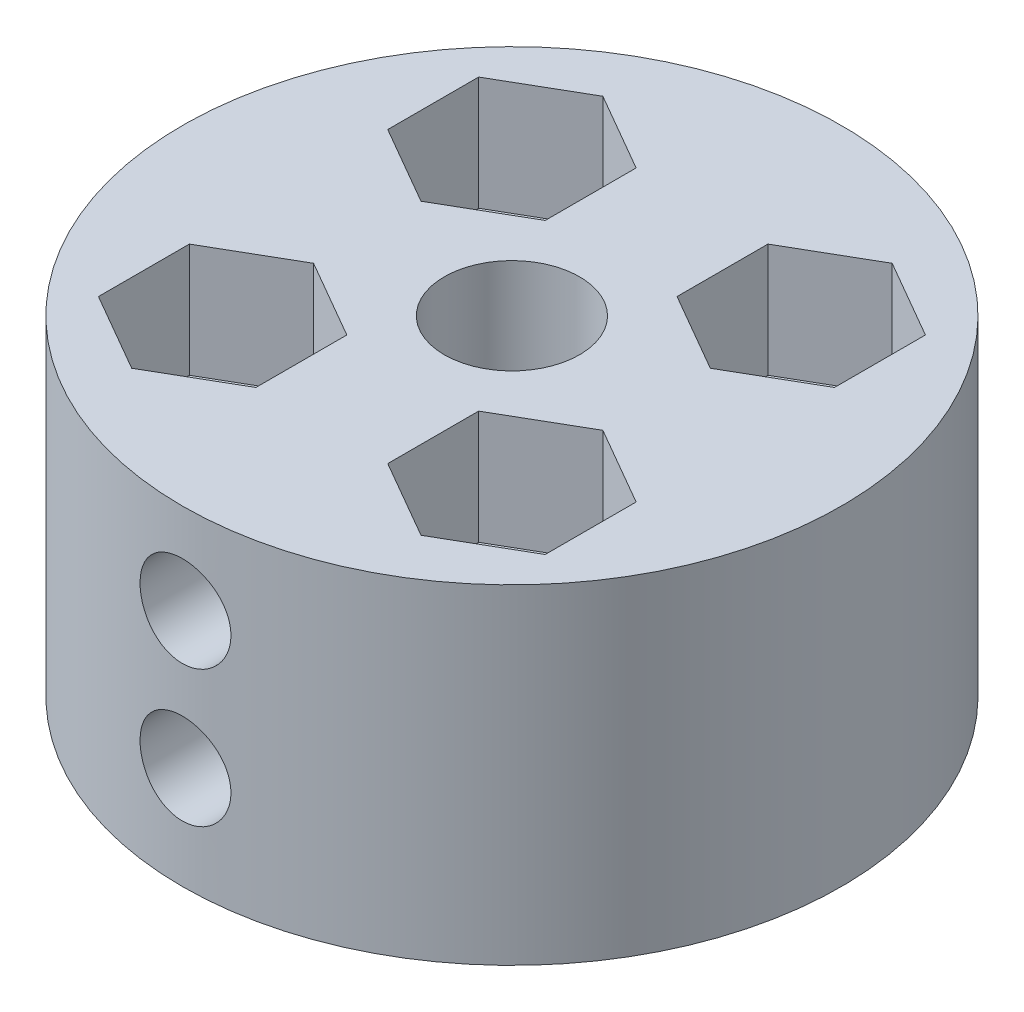
SolidWorks part; units mm, degrees
material "3.0205 (EN-AW 1200)"
ref_plane "Alzado" through (0, 0, 0) normal (0, 0, 1) x (1, 0, 0)
ref_plane "Planta" through (0, 0, 0) normal (0, 1, 0) x (1, 0, 0)
ref_plane "Vista lateral" through (0, 0, 0) normal (1, 0, 0) x (0, 0, -1)
sketch "Croquis1" plane through (0, 0, 0) normal (0, 1, 0) x (1, 0, 0)
  circle A0 centre (0, 0) radius 14.5
  dimension "D1" = 29
extrude "Saliente-Extruir1" add sketch "Croquis1" along normal blind 14.5
sketch "Croquis2" plane through (0, 14.5, 0) normal (0, 1, 0) x (1, 0, 0)
  line L0 (-1.61, -2.5017) -> (1.61, -2.5017)
  arc A1 (1.61, -2.5017) -> (-1.61, -2.5017) centre (0, 0) ccw
  dimension "D1" = 3.22
  dimension "D2" = 5.95
extrude "Cortar-Extruir1" cut sketch "Croquis2" against normal through all
sketch "Croquis3" plane through (0, 14.5, 0) normal (0, 1, 0) x (1, 0, 0)
  line L1 (-6.364, -6.364) -> (6.364, -6.364)
  line L2 (-6.364, -6.364) -> (-6.364, 6.364)
  line L3 (-6.364, 6.364) -> (6.364, 6.364)
  line L4 (6.364, -6.364) -> (6.364, 6.364)
  line L5 (-6.364, -6.364) -> (6.364, 6.364) construction
  line L6 (-6.364, 6.364) -> (6.364, -6.364) construction
  circle A0 centre (-6.364, 6.364) radius 2
  circle A1 centre (6.364, 6.364) radius 2
  circle A2 centre (6.364, -6.364) radius 2
  circle A3 centre (-6.364, -6.364) radius 2
  point P0 (0, 0)
  dimension "D3" = 4
  dimension "D1" = 12.728
  dimension "D2" = 12.728
extrude "Cortar-Extruir2" cut sketch "Croquis3" against normal through all contours L3 A0 L2 | L2 A0 L3 | L2 A3 L1 | L1 A3 L2 | L4 A2 L1 | L1 A2 L4 | L3 A1 L4 | L4 A1 L3
sketch "Croquis5" plane through (0, 14.5, 0) normal (0, 1, 0) x (1, 0, 0)
  line L1 (-6.364, 2.364) -> (-2.8999, 4.364)
  line L2 (-2.8999, 4.364) -> (-2.8999, 8.364)
  line L3 (-2.8999, 8.364) -> (-6.364, 10.364)
  line L4 (-6.364, 10.364) -> (-9.8281, 8.364)
  line L5 (-9.8281, 8.364) -> (-9.8281, 4.364)
  line L6 (-9.8281, 4.364) -> (-6.364, 2.364)
  circle A0 centre (-6.364, 6.364) radius 4 construction
  dimension "D1" = 4
extrude "Cortar-Extruir3" cut sketch "Croquis5" against normal blind 5
pattern_linear "MatrizL1" count 2 spacing 12.728 along (1, 0, 0) count 2 spacing 12.728 along (0, 0, 1) of "Cortar-Extruir3"
ref_plane "Plano1" through (0, 0, 14.5) normal (0, 0, 1) x (1, 0, 0)
sketch "Croquis6" plane through (0, 0, 14.5) normal (0, 0, 1) x (1, 0, 0)
  line L1 (14.5, 14.5) -> (-14.5, 14.5) construction
  circle A0 centre (0, 10.5) radius 2
  circle A1 centre (0, 4.5) radius 2
  dimension "D1" = 4
  dimension "D2" = 4
  dimension "D3" = 6
extrude "Cortar-Extruir4" cut sketch "Croquis6" against normal up to surface (11.9983 mm away) up to face at (0, 7.25, 2.5017)
sketch "Croquis9" plane through (0, 0, 2.5017) normal (0, 0, 1) x (1, 0, 0)
  line L0 (-1.61, 11.6865) -> (-1.61, 9.3135)
  line L1 (-1.61, 9.3135) -> (-1.61, 11.6865) construction
  line L2 (1.61, 11.6865) -> (1.61, 9.3135)
  line L3 (-1.61, 5.6865) -> (-1.61, 3.3135)
  line L4 (1.61, 5.6865) -> (1.61, 3.3135)
  arc A0 (1.61, 9.3135) -> (1.61, 11.6865) centre (0, 10.5) ccw
  arc A1 (-1.61, 11.6865) -> (-1.61, 9.3135) centre (0, 10.5) ccw
  arc A2 (-1.61, 5.6865) -> (-1.61, 3.3135) centre (0, 4.5) ccw
  arc A3 (1.61, 3.3135) -> (1.61, 5.6865) centre (0, 4.5) ccw
extrude "Cortar-Extruir5" cut sketch "Croquis9" against normal blind 1
sketch "Croquis11" plane through (0, 14.5, 0) normal (0, 1, 0) x (1, 0, 0)
  line L0 (-1.61, -2.5017) -> (1.61, -2.5017)
  circle A0 centre (0, 0) radius 2.975
  line M28 (1.61, -2.5017) -> (-1.61, -2.5017)
extrude "Cortar-Extruir9" cut sketch "Croquis11" against normal blind 1.9 contours A0 M28
